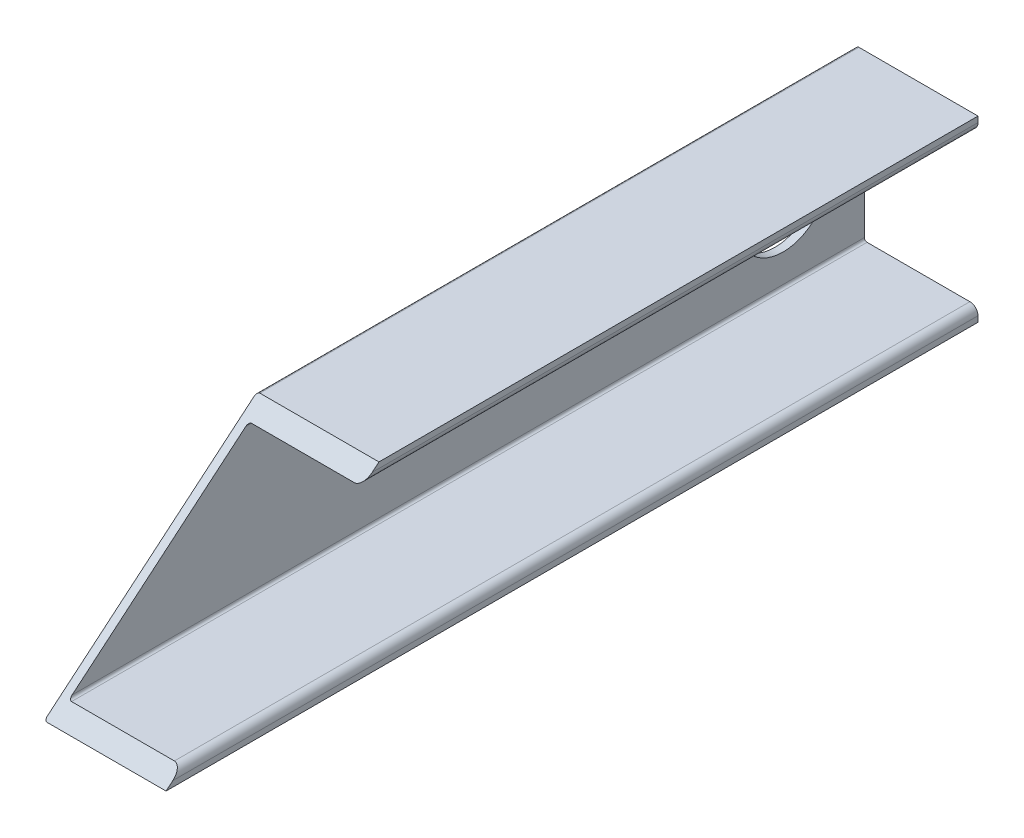
SolidWorks part; units mm, degrees
material "Gray Cast Iron"
ref_plane "Front Plane" through (0, 0, 0) normal (0, 0, 1) x (1, 0, 0)
ref_plane "Top Plane" through (0, 0, 0) normal (0, 1, 0) x (1, 0, 0)
ref_plane "Right Plane" through (0, 0, 0) normal (1, 0, 0) x (0, 0, -1)
sketch "Sketch1" plane through (0, 0, 0) normal (0, 0, 1) x (1, 0, 0)
  line L0 (0, 33) -> (0, -33)
  line L1 (0, -33) -> (45, -33)
  line L2 (0, 33) -> (45, 33)
  line L3 (45, -33) -> (45, -27.9)
  line L4 (45, -27.9) -> (3, -27.9)
  line L5 (3, -27.9) -> (3, 27.9)
  line L6 (3, 27.9) -> (45, 27.9)
  line L7 (45, 27.9) -> (45, 33)
  point P4 (0, 0)
  dimension "D1" = 66
  dimension "D2" = 45
  dimension "D3" = 45
  dimension "D4" = 5.1
  dimension "D5" = 5.1
  dimension "D6" = 42
extrude "Boss-Extrude1" add sketch "Sketch1" along normal blind 300
sketch "Sketch3" plane through (0, 0, 0) normal (-1, 0, 0) x (0, 0, 1)
  line L0 (300, -33) -> (221.3443, 33)
  line L1 (300, 33) -> (0, 33) construction
  line L2 (221.3443, 33) -> (300, 33)
  line L3 (300, 33) -> (300, -33)
  dimension "D1" = 50
extrude "Cut-Extrude1" cut sketch "Sketch3" against normal up to next
fillet "Fillet1" radius 3 2 edges at (45, -27.9, 146.961) (45, 27.9, 113.7111)
fillet "Fillet2" radius 1 4 edges at (3, -27.9, 146.961) (0, -33, 150) (0, 33, 110.6721) (3, 27.9, 113.7111)
sketch "Sketch7" plane through (0, 0, 0) normal (-1, 0, 0) x (0, 0, 1)
  line L0 (0, 0) -> (260.6721, 0) construction
  line L1 (222.536, 32) -> (298.8082, -32) construction
  line L2 (0, 32) -> (0, -32) construction
  circle A0 centre (30, 0) radius 16.5
  dimension "D1" = 33
  dimension "D2" = 30
extrude "Cut-Extrude4" cut sketch "Sketch7" against normal blind 50
